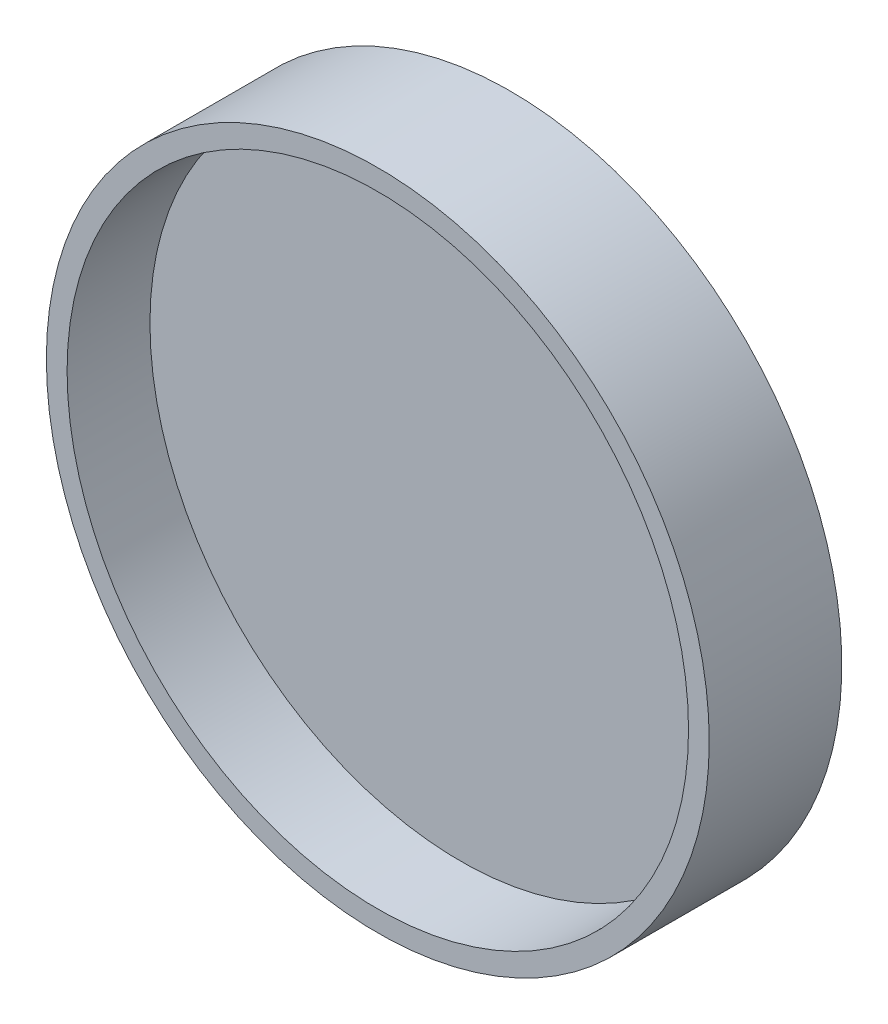
SolidWorks part; units mm, degrees
material "1060-H12"
ref_plane "Front Plane" through (0, 0, 0) normal (0, 0, 1) x (1, 0, 0)
ref_plane "Top Plane" through (0, 0, 0) normal (0, 1, 0) x (1, 0, 0)
ref_plane "Right Plane" through (0, 0, 0) normal (1, 0, 0) x (0, 0, -1)
sketch "Szkic1" plane through (0, 0, 0) normal (0, 0, 1) x (1, 0, 0)
  circle A0 centre (0, 0) radius 80
  dimension "D1" = 160
extrude "Dodanie-wyciągnięcie1" add sketch "Szkic1" along normal blind 30 contours A0
sketch "Szkic2" plane through (0, 0, 30) normal (0, 0, 1) x (1, 0, 0)
  circle A1 centre (0, 0) radius 75
  point P0 (0, 0)
  dimension "D1" = 150
extrude "Wytnij-wyciągnięcie2" cut sketch "Szkic2" against normal blind 20 contours A1
cosmetic thread "Oznaczenie gwintu1" parameters "D1"=20, "D2"=151
sketch "Szkic20" plane through (0, 0, 0) normal (0, 0, -1) x (-1, 0, 0)
  circle A1 centre (0, 0) radius 80
  circle A2 centre (0, 0) radius 80
  dimension "D1" = 0
extrude "Dodanie-wyciągnięcie2" add sketch "Szkic20" along normal blind 22
sketch "Szkic21" plane through (0, 0, 0) normal (0, 1, 0) x (1, 0, 0)
  line L0 (75, -30) -> (-75, -30) construction
  line L1 (-75, -30) -> (-80, -30) construction
  line L2 (-80, -30) -> (-80, 20) construction
  line L4 (80, 20) -> (80, -30) construction
  line L5 (80, -30) -> (75, -30) construction
  line L6 (0, 0) -> (0, -50000) construction
  line L7 (75, -30) -> (-75, -30)
  line L8 (0, 22) -> (-13.9951, 22)
  line L9 (-13.9951, 22) -> (-10.6003, 20.04)
  line L10 (-10.6003, 20.04) -> (-5, 10.34)
  line L11 (-5, 10.34) -> (-5, -2.46)
  line L12 (-5, -2.46) -> (0, -7.46)
  line L13 (0, 22) -> (0, -7.46)
  line L14 (-75, -30) -> (-80, -30)
  line L15 (-80, -30) -> (-80, 22)
  line L16 (-80, 22) -> (80, 22) construction
  line L17 (80, 22) -> (80, -30)
  line L18 (80, -30) -> (75, -30)
  dimension "D1" = 12.8
  dimension "D2" = 1.96
  dimension "D3" = 5
  dimension "D4" = 30
  dimension "D5" = 29.46
  dimension "D6" = 60
  dimension "D7" = 45
  dimension "D8" = 13.9951
revolve "Wycięcie-obrót1" cut sketch "Szkic21" angle 360 about L6
sketch "Szkic22" plane through (0, 0, -22) normal (0, 0, -1) x (-1, 0, 0)
  circle A0 centre (0, 0) radius 34.425
  circle A1 centre (0, 0) radius 80 construction
  circle A2 centre (0, 0) radius 80
  dimension "D1" = 68.85
extrude "Wytnij-wyciągnięcie3" cut sketch "Szkic22" against normal blind 20
